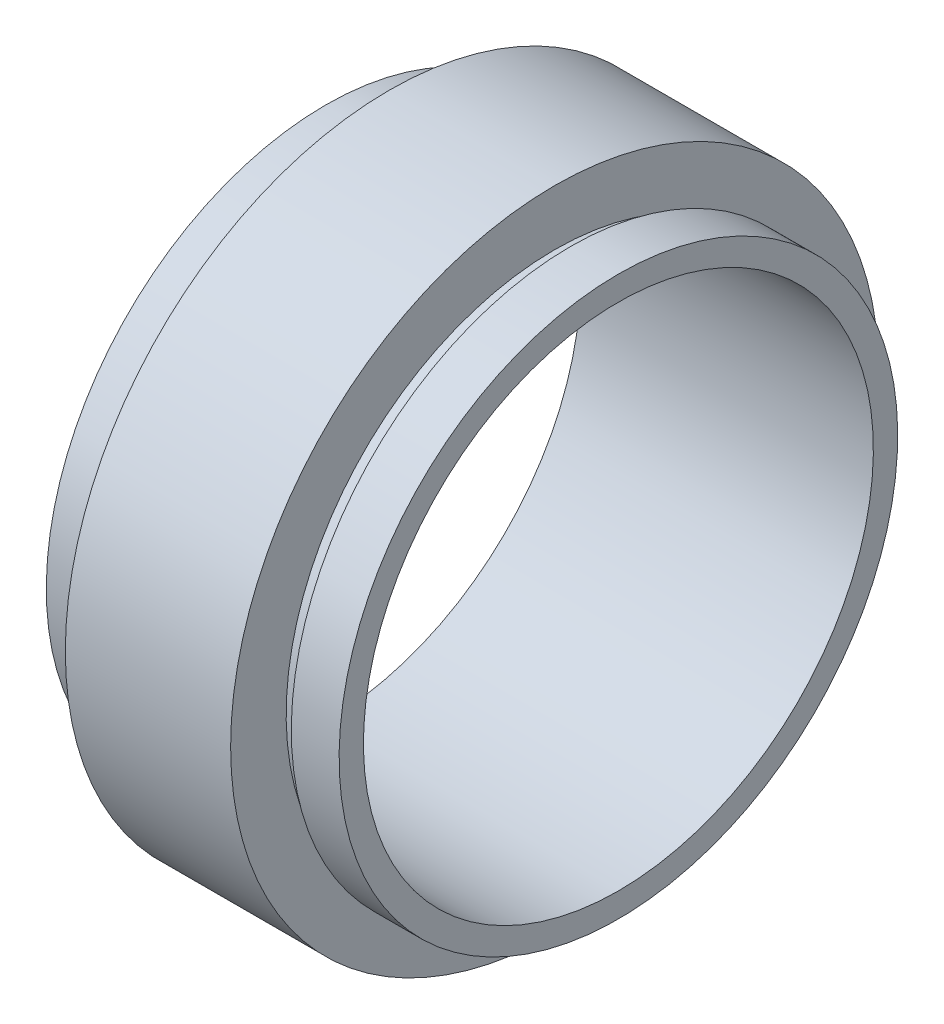
SolidWorks part; units mm, degrees
ref_plane "Front Plane" through (0, 0, 0) normal (0, 0, 1) x (1, 0, 0)
ref_plane "Top Plane" through (0, 0, 0) normal (0, 1, 0) x (1, 0, 0)
ref_plane "Right Plane" through (0, 0, 0) normal (1, 0, 0) x (0, 0, -1)
sketch "Sketch2" plane through (0, 0, 0) normal (0, 0, 1) x (1, 0, 0)
  line L0 (6.89, 0) -> (-6.89, 0)
  line L1 (-6.89, 0) -> (-6.89, 13.1445)
  line L2 (-6.89, 13.1445) -> (-4.64, 13.1445)
  line L3 (-4.64, 13.1445) -> (-4.64, 12.6365)
  line L4 (-4.64, 12.6365) -> (-3.89, 12.6365)
  line L5 (-3.89, 12.6365) -> (-3.89, 15.25)
  line L6 (-3.89, 15.25) -> (3.89, 15.25)
  line L7 (3.89, 15.25) -> (3.89, 12.6365)
  line L8 (3.89, 12.6365) -> (4.64, 12.6365)
  line L9 (4.64, 12.6365) -> (4.64, 13.1445)
  line L10 (4.64, 13.1445) -> (6.89, 13.1445)
  line L11 (6.89, 13.1445) -> (6.89, 0)
  point P3 (0, 15.25)
  dimension "D1" = 15.25
  dimension "D2" = 13.1445
  dimension "D3" = 0.508
  dimension "D4" = 7.78
  dimension "D5" = 0.75
  dimension "D6" = 3
revolve "Revolve1" add sketch "Sketch2" angle 360 about L0
sketch "Sketch3" plane through (-6.89, 0, 0) normal (-1, 0, 0) x (0, 0, 1)
  circle A0 centre (0, 0) radius 12
  dimension "D1" = 24
extrude "Cut-Extrude1" cut sketch "Sketch3" against normal through all
